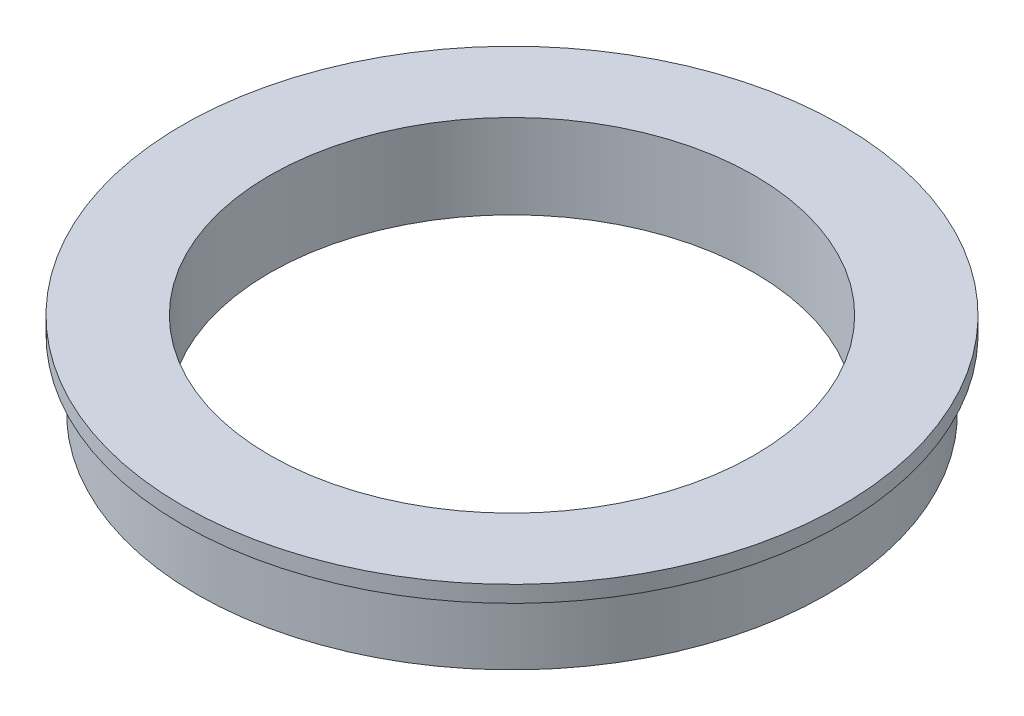
SolidWorks part; units mm, degrees
ref_plane "前视基准面" through (0, 0, 0) normal (0, 0, 1) x (1, 0, 0)
ref_plane "上视基准面" through (0, 0, 0) normal (0, 1, 0) x (1, 0, 0)
ref_plane "右视基准面" through (0, 0, 0) normal (1, 0, 0) x (0, 0, -1)
other "Configuration Table"
sketch "草图1" plane through (0, 0, 0) normal (0, 1, 0) x (1, 0, 0)
  circle A0 centre (0, 0) radius 32.5
  circle A1 centre (0, 0) radius 25
  dimension "D1" = 65
  dimension "D2" = 50
extrude "凸台-拉伸1" add sketch "草图1" along normal blind 7
sketch "草图2" plane through (0, 7, 0) normal (0, 1, 0) x (1, 0, 0)
  circle A0 centre (0, 0) radius 34
  circle A1 centre (0, 0) radius 25
  dimension "D1" = 68
extrude "凸台-拉伸2" add sketch "草图2" along normal blind 1.7
